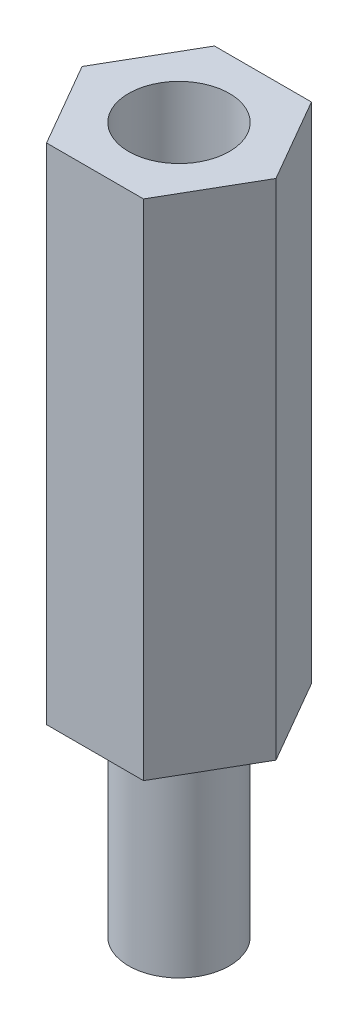
SolidWorks part; units mm, degrees
material "Latón"
ref_plane "Alzado" through (0, 0, 0) normal (0, 0, 1) x (1, 0, 0)
ref_plane "Planta" through (0, 0, 0) normal (0, 1, 0) x (1, 0, 0)
ref_plane "Vista lateral" through (0, 0, 0) normal (1, 0, 0) x (0, 0, -1)
sketch "Croquis1" plane through (0, 0, 0) normal (0, 1, 0) x (1, 0, 0)
  line L1 (1.4434, -2.5) -> (2.8868, 0)
  line L2 (2.8868, 0) -> (1.4434, 2.5)
  line L3 (1.4434, 2.5) -> (-1.4434, 2.5)
  line L4 (-1.4434, 2.5) -> (-2.8868, 0)
  line L5 (-2.8868, 0) -> (-1.4434, -2.5)
  line L6 (-1.4434, -2.5) -> (1.4434, -2.5)
  circle A0 centre (0, 0) radius 2.5 construction
  circle A1 centre (0, 0) radius 1.5
  dimension "D2" = 3
  dimension "D1" = 5
extrude "Saliente-Extruir1" add sketch "Croquis1" along normal blind 15
sketch "Croquis2" plane through (0, 0, 0) normal (0, -1, 0) x (1, 0, 0)
  circle A0 centre (0, 0) radius 1.5 construction
  circle A1 centre (0, 0) radius 1.5
extrude "Saliente-Extruir2" add sketch "Croquis2" along normal blind 6 separate body
